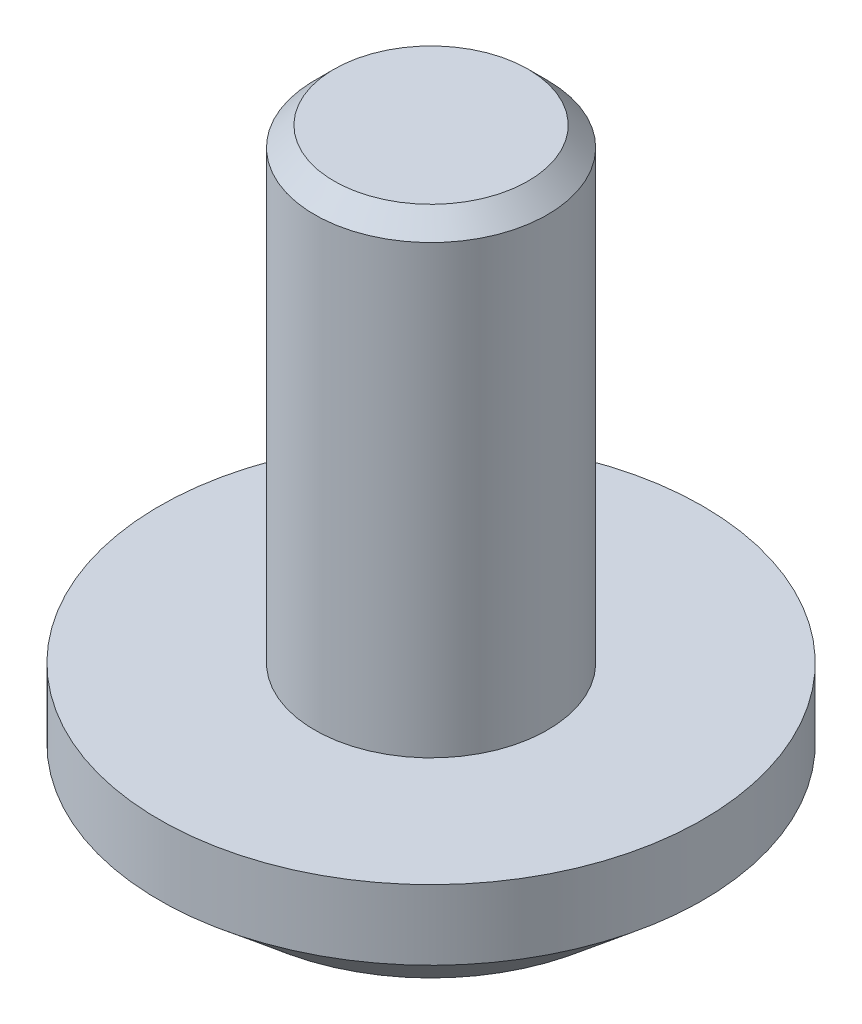
SolidWorks part; units mm, degrees
material "AISI 304"
ref_plane "前视基准面" through (0, 0, 0) normal (0, 0, 1) x (1, 0, 0)
ref_plane "上视基准面" through (0, 0, 0) normal (0, 1, 0) x (1, 0, 0)
ref_plane "右视基准面" through (0, 0, 0) normal (1, 0, 0) x (0, 0, -1)
other "Configuration Table"
sketch "草图1" plane through (0, 0, 0) normal (0, 0, 1) x (1, 0, 0)
  line L0 (0, -1003.6) -> (0, -1.8) construction
  line L1 (1.5, 0) -> (1.5, 5.75)
  line L2 (1.5, 5.75) -> (1.25, 6)
  line L3 (1.25, 6) -> (0, 6)
  line L4 (0, 6) -> (0, 0)
  line L5 (1, -1.8) -> (2.4274, -1.8)
  line L6 (2.4274, -1.8) -> (3.5, -0.9)
  line L7 (3.5, -0.9) -> (3.5, 0)
  line L8 (3.5, 0) -> (1.5, 0)
  line L9 (0, 0) -> (1, -0.6009)
  line L10 (1, -0.6009) -> (1, -1.8)
  line L11 (0, 0) -> (0, 4006.9635) construction
  dimension "M" = 3
  dimension "d" = 2.5
  dimension "D1" = 45
  dimension "Dk" = 7
  dimension "k" = 1.8
  dimension "alpha" = 50
  dimension "D2" = 0.9
  dimension "theta" = 59
  dimension "D3" = 2
revolve "旋转1" add sketch "草图1" angle 360 about L11
sketch "草图2" plane through (0, -1.8, 0) normal (0, -1, 0) x (1, 0, 0)
  line L1 (1.1547, 0) -> (0.5774, 1)
  line L2 (0.5774, 1) -> (-0.5774, 1)
  line L3 (-0.5774, 1) -> (-1.1547, 0)
  line L4 (-1.1547, 0) -> (-0.5774, -1)
  line L5 (-0.5774, -1) -> (0.5774, -1)
  line L6 (0.5774, -1) -> (1.1547, 0)
  circle A0 centre (0, 0) radius 1 construction
  circle A1 centre (0, 0) radius 1 construction
extrude "切除-拉伸1" cut sketch "草图2" against normal up to surface (1.1062 mm away)
move or copy body "实体-移动/复制1" [suppressed] bodies to move or copy 107
equation "\"D2@草图1\"= 0.5 * \"k@草图1\""
